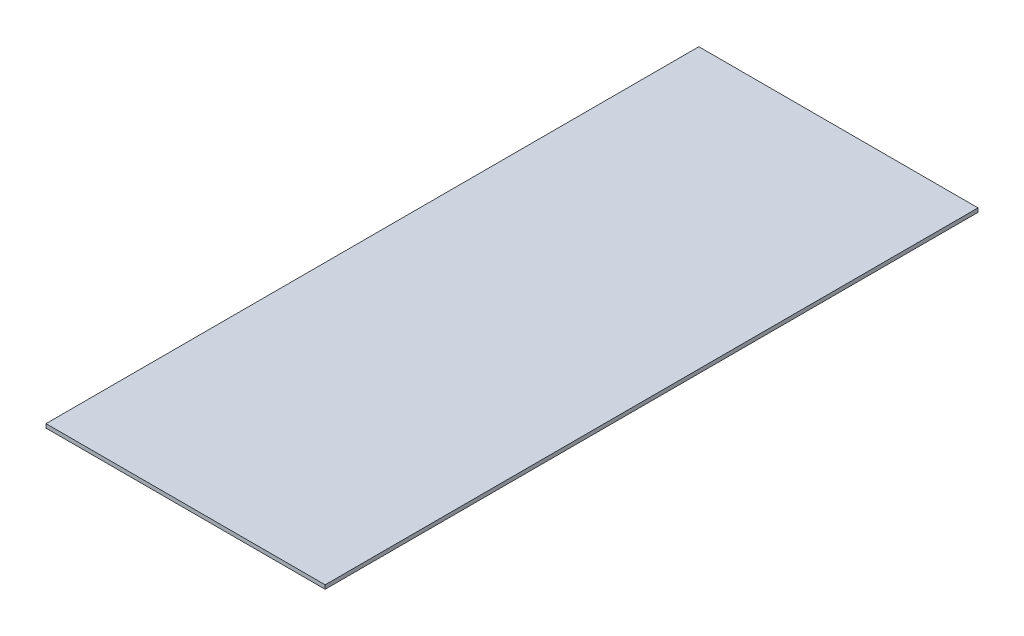
SolidWorks part; units mm, degrees
ref_plane "Front Plane" through (0, 0, 0) normal (0, 0, 1) x (1, 0, 0)
ref_plane "Top Plane" through (0, 0, 0) normal (0, 1, 0) x (1, 0, 0)
ref_plane "Right Plane" through (0, 0, 0) normal (1, 0, 0) x (0, 0, -1)
sketch "Sketch1" plane through (0, 0, 0) normal (0, 1, 0) x (1, 0, 0)
  line L1 (0, 0) -> (393.7, 0)
  line L2 (0, 0) -> (0, -920.75)
  line L3 (0, -920.75) -> (393.7, -920.75)
  line L4 (393.7, 0) -> (393.7, -920.75)
  dimension "D1" = 393.7
  dimension "D2" = 920.75
extrude "Boss-Extrude1" add sketch "Sketch1" along normal blind 5.5
